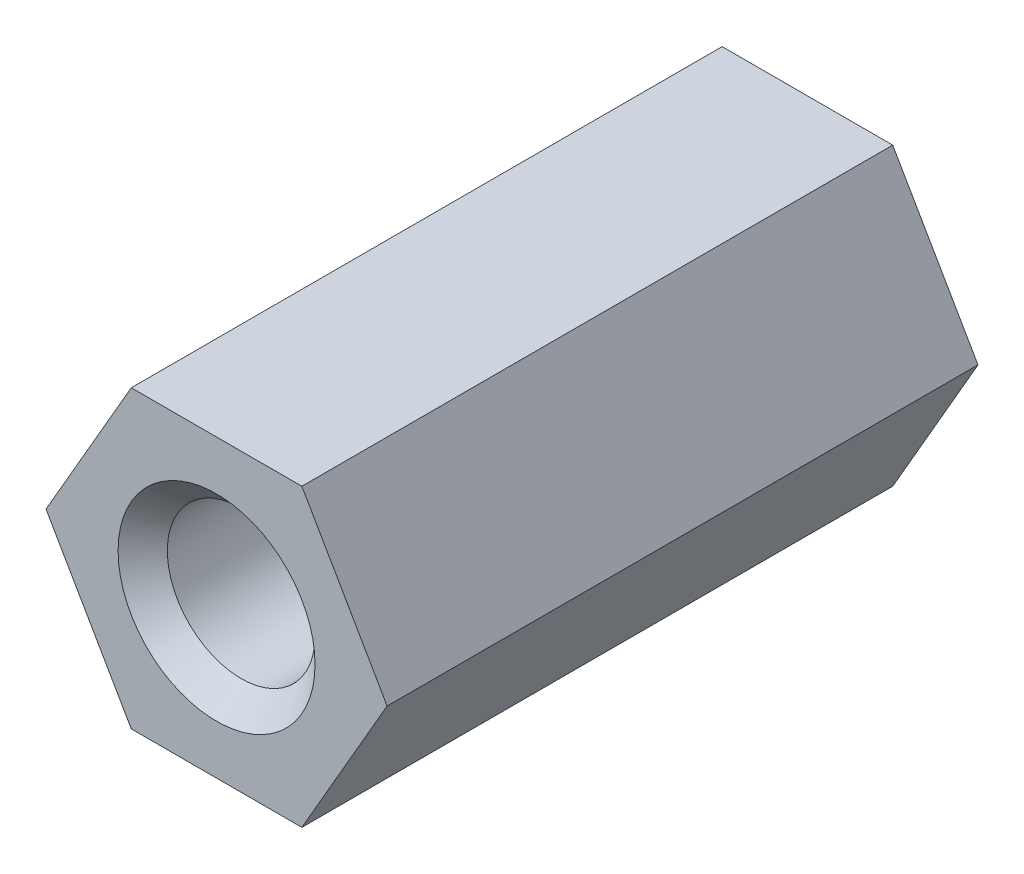
SolidWorks part; units mm, degrees
ref_plane "Top Plane" through (0, 0, 0) normal (0, 0, 1) x (1, 0, 0)
ref_plane "Right Plane" through (0, 0, 0) normal (0, 1, 0) x (1, 0, 0)
ref_plane "Front Plane" through (0, 0, 0) normal (1, 0, 0) x (0, 0, -1)
sketch "Sketch1" plane through (0, 0, 0) normal (0, 0, 1) x (1, 0, 0)
  line L1 (3.4641, 0) -> (1.7321, 3)
  line L2 (1.7321, 3) -> (-1.7321, 3)
  line L3 (-1.7321, 3) -> (-3.4641, 0)
  line L4 (-3.4641, 0) -> (-1.7321, -3)
  line L5 (-1.7321, -3) -> (1.7321, -3)
  line L6 (1.7321, -3) -> (3.4641, 0)
  circle A0 centre (0, 0) radius 3 construction
  circle A1 centre (0, 0) radius 1.5
  dimension "D2" = 3
  dimension "D1" = 6
extrude "Boss-Extrude1" add sketch "Sketch1" along normal mid plane 12
chamfer "Chamfer1" distance 0.5 angle 45 1 edges at (1.5, 0, 6)
